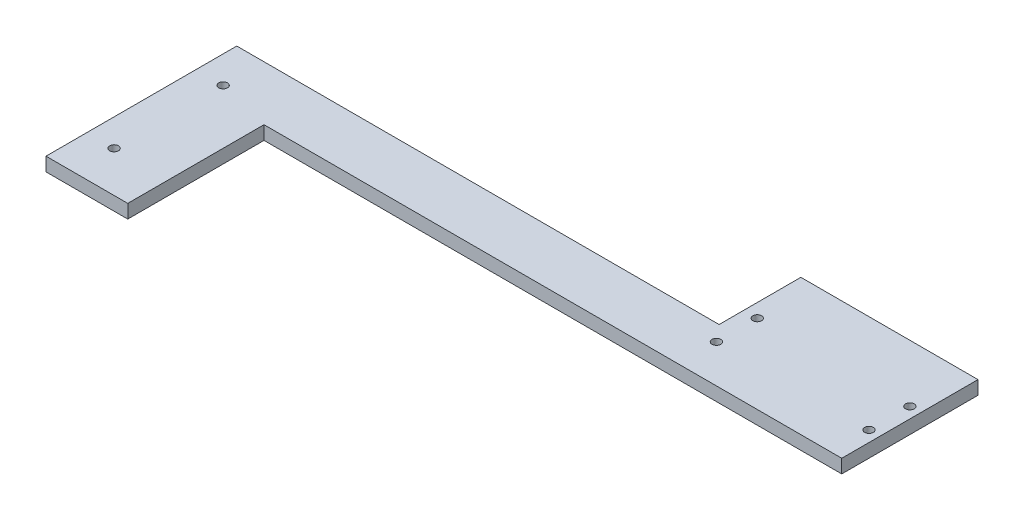
SolidWorks part; units mm, degrees
ref_plane "前视基准面" through (0, 0, 0) normal (0, 0, 1) x (1, 0, 0)
ref_plane "上视基准面" through (0, 0, 0) normal (0, 1, 0) x (1, 0, 0)
ref_plane "右视基准面" through (0, 0, 0) normal (1, 0, 0) x (0, 0, -1)
sketch "草图1" plane through (0, 0, 0) normal (0, 1, 0) x (1, 0, 0)
  line L0 (0, 140.5035) -> (0, -140.5035) construction
  line L1 (-140.5035, 0) -> (20, 0) construction
  line L3 (172, 44) -> (228, 44) construction
  line L4 (172, 44) -> (172, 29) construction
  line L5 (172, 29) -> (228, 29) construction
  line L6 (228, 44) -> (228, 29) construction
  line L7 (172, 44) -> (228, 29) construction
  line L8 (172, 29) -> (228, 44) construction
  line L9 (-10, 35) -> (0, 35)
  line L12 (-10, 35) -> (-10, -35)
  line L13 (232, 15) -> (232, 65)
  line L14 (0, 35) -> (167, 35)
  line L15 (167, 35) -> (167, 65)
  line L16 (167, 65) -> (232, 65)
  line L17 (-10, -35) -> (0, -35)
  line L18 (0, -35) -> (20, -35)
  line L19 (20, -35) -> (20, 0)
  line L21 (20, 0) -> (20, 15)
  line L22 (20, 15) -> (232, 15)
  circle A0 centre (0, -20) radius 1.6
  circle A2 centre (0, 20) radius 1.6
  circle A3 centre (172, 29) radius 1.6
  circle A4 centre (172, 44) radius 1.6
  circle A5 centre (228, 29) radius 1.6
  circle A6 centre (228, 44) radius 1.6
  point P10 (200, 36.5)
  point P24 (-10, 0)
  point P26 (-10, 0)
  dimension "D1" = 3.2
  dimension "D5" = 200
  dimension "D6" = 3.2
  dimension "D2" = 20
  dimension "D3" = 15
  dimension "D4" = 56
  dimension "D7" = 36.5
  dimension "D8" = 10
  dimension "D9" = 242
  dimension "D10" = 30
  dimension "D11" = 35
  dimension "D12" = 5
  dimension "D13" = 20
  dimension "D14" = 15
extrude "凸台-拉伸1" add sketch "草图1" along normal blind 5
